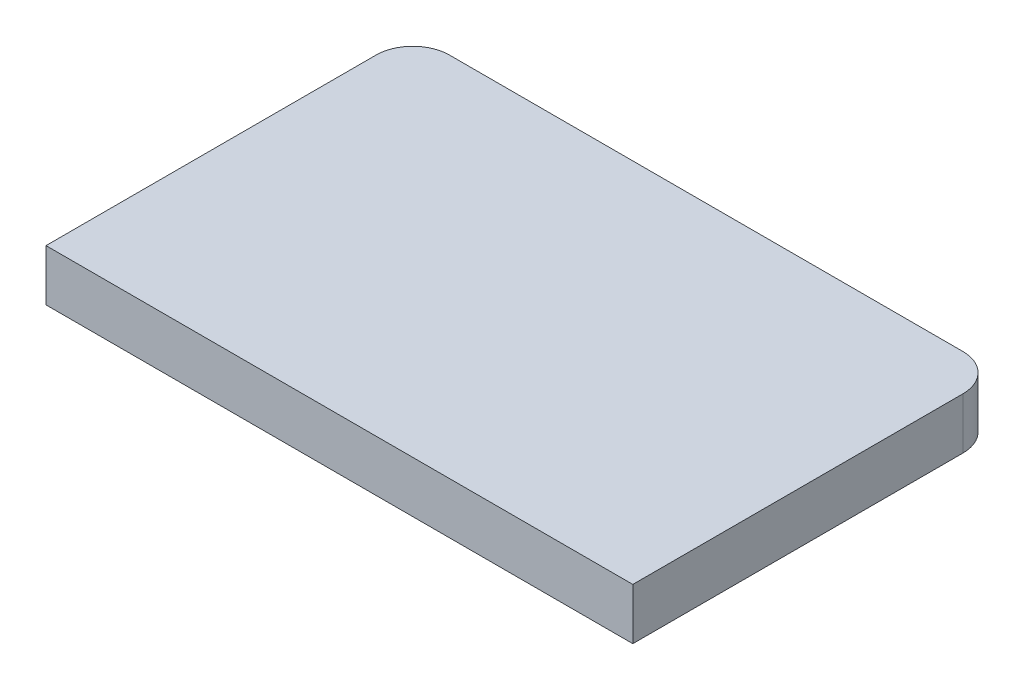
SolidWorks part; units mm, degrees
material "Pine"
ref_plane "Front Plane" through (0, 0, 0) normal (0, 0, 1) x (1, 0, 0)
ref_plane "Top Plane" through (0, 0, 0) normal (0, 1, 0) x (1, 0, 0)
ref_plane "Right Plane" through (0, 0, 0) normal (1, 0, 0) x (0, 0, -1)
sketch "Sketch1" plane through (0, 0, 0) normal (0, 0, 1) x (1, 0, 0)
  line L1 (127, 76.2) -> (-127, 76.2)
  line L2 (127, 76.2) -> (127, -76.2)
  line L3 (127, -76.2) -> (-127, -76.2)
  line L4 (-127, 76.2) -> (-127, -76.2)
  line L5 (127, 76.2) -> (-127, -76.2) construction
  line L6 (127, -76.2) -> (-127, 76.2) construction
  circle A0 centre (0, 0) radius 6.35
  point P0 (0, 0)
  dimension "D1" = 254
  dimension "D2" = 152.4
sketch "Sketch2" plane through (0, 0, 0) normal (0, 1, 0) x (1, 0, 0)
  line L1 (-101.6, 63.5) -> (101.6, 63.5)
  line L2 (-101.6, 63.5) -> (-101.6, -63.5)
  line L3 (-101.6, -63.5) -> (101.6, -63.5)
  line L4 (101.6, 63.5) -> (101.6, -63.5)
  line L5 (-101.6, 63.5) -> (101.6, -63.5) construction
  line L6 (-101.6, -63.5) -> (101.6, 63.5) construction
  point P0 (0, 0)
  dimension "D1" = 203.2
  dimension "D2" = 127
extrude "Boss-Extrude2" add sketch "Sketch2" along normal blind 17.78
fillet "Fillet1" radius 12.7 2 edges at (-101.6, 8.89, -63.5) (101.6, 8.89, -63.5)
sketch "Sketch5" plane through (0, 0, 0) normal (0, -1, 0) x (1, 0, 0)
  line L0 (-101.6, 63.5) -> (101.6, 63.5) construction
  line L1 (101.6, 63.5) -> (101.6, -50.8) construction
  line L2 (-101.6, -50.8) -> (-101.6, 63.5) construction
  circle A0 centre (50.8, 49.8348) radius 2.0828
  circle A1 centre (33.5788, 25.0698) radius 2.0828
  circle A2 centre (-50.8, 25.0698) radius 2.0828
  circle A3 centre (-33.5788, 49.8348) radius 2.0828
  dimension "D1" = 4.1656
  dimension "D2" = 13.6652
  dimension "D3" = 38.4302
  dimension "D4" = 17.2212
  dimension "D5" = 38.4302
  dimension "D6" = 13.6652
  dimension "D7" = 17.2212
  dimension "D8" = 50.8
  dimension "D9" = 50.8
extrude "Cut-Extrude2" cut sketch "Sketch5" against normal blind 12.7
